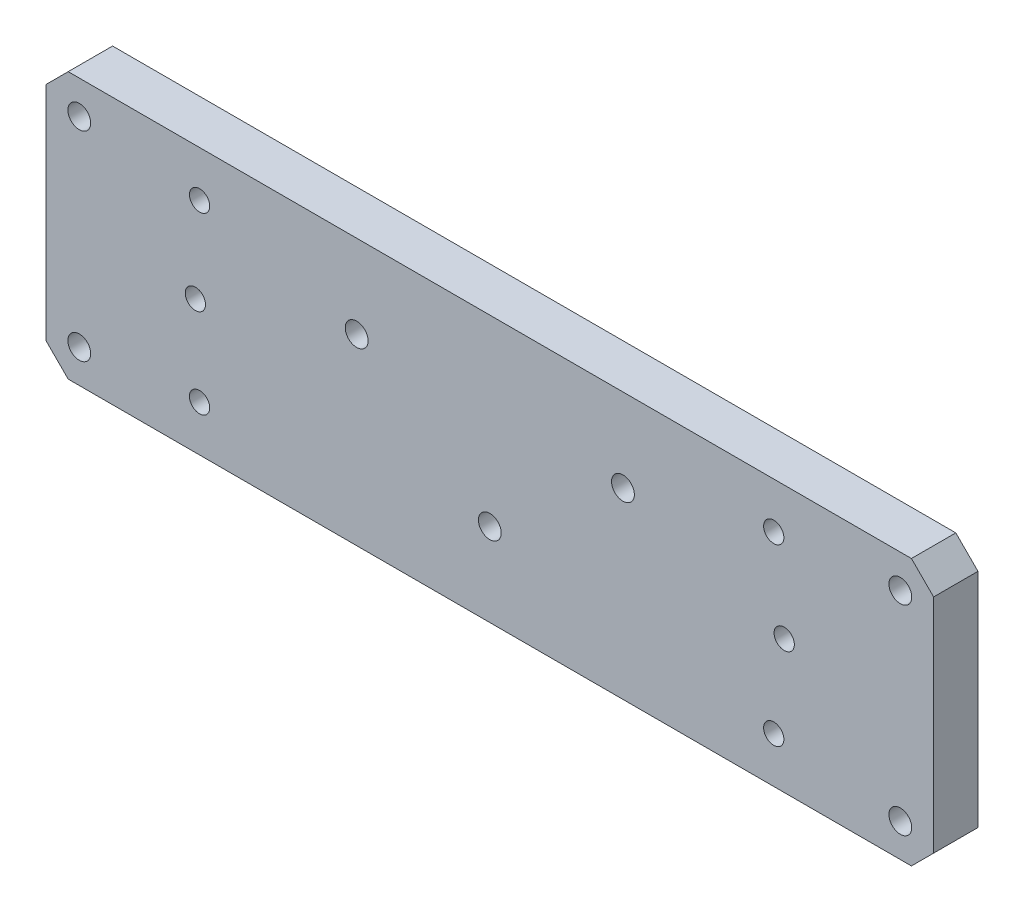
SolidWorks part; units mm, degrees
material "6061-T6 (SS)"
ref_plane "Front Plane" through (0, 0, 0) normal (0, 0, 1) x (1, 0, 0)
ref_plane "Top Plane" through (0, 0, 0) normal (0, 1, 0) x (1, 0, 0)
ref_plane "Right Plane" through (0, 0, 0) normal (1, 0, 0) x (0, 0, -1)
sketch "Sketch1" plane through (0, 0, 0) normal (0, 0, 1) x (1, 0, 0)
  line L1 (127, -38.1) -> (-127, -38.1)
  line L2 (127, -38.1) -> (127, 38.1)
  line L3 (127, 38.1) -> (-127, 38.1)
  line L4 (-127, -38.1) -> (-127, 38.1)
  line L5 (127, -38.1) -> (-127, 38.1) construction
  line L6 (127, 38.1) -> (-127, -38.1) construction
  point P0 (0, 0)
  dimension "D1" = 254
  dimension "D2" = 76.2
extrude "Boss-Extrude1" add sketch "Sketch1" along normal blind 12.7
hole_wizard "1/4 Clearance Hole1" positions "Sketch2" profile "Sketch3" hole size "1/4" standard "ANSI Inch" end condition through all
sketch "Sketch2" plane through (0, 0, 12.7) normal (0, 0, 1) x (1, 0, 0)
  line L0 (-117.475, 38.1) -> (-117.475, -38.1) construction
  line L4 (0, 38.1) -> (0, 0) construction
  line L5 (0, 0) -> (-117.475, 0) construction
  line L7 (-38.1, 0) -> (-38.1, 14.2875) construction
  line L9 (0, 0) -> (0, -14.2875) construction
  line L11 (-117.475, 28.575) -> (-117.475, 0)
  line L13 (-117.475, 14.2875) -> (-38.1, 14.2875) construction
  point P9 (-117.475, -28.575)
  point P11 (-117.475, 28.575)
  point P24 (117.475, -28.575)
  point P26 (117.475, 28.575)
  point P35 (-38.1, 14.2875)
  point P40 (0, -14.2875)
  point P55 (38.1, 14.2875)
sketch "Sketch3" plane through (38.1, 14.2875, 12.7) normal (1, 0, 0) x (0, -1, 0)
  line L0 (0, 0) -> (0, 12.7)
  line L1 (0, 12.7) -> (3.2639, 12.7)
  line L2 (3.2639, 12.7) -> (3.2639, 0)
  line L3 (3.2639, 0) -> (0, 0)
  line L4 (0, -6.35) -> (0, 107.95) construction
  dimension "Thru Hole Dia." = 6.5278
  dimension "Thru Hole Depth" = 12.7
chamfer "Chamfer1" distance 6.35 angle 45 4 edges at (127, 38.1, 6.35) (127, -38.1, 6.35) (-127, 38.1, 6.35) (-127, -38.1, 6.35)
hole_wizard "CSK for M5 Flat Head Machine Screw1" positions "Sketch6" profile "Sketch7" countersink size "M5" standard "ANSI Metric" end condition through all
sketch "Sketch6" plane through (0, 0, 0) normal (0, 0, -1) x (-1, 0, 0)
  line L0 (-81.25, 25) -> (-81.25, -25) construction
  line L1 (83.05, 25) -> (83.05, -25) construction
  point P0 (-81.25, -25)
  point P1 (-81.25, 25)
  point P2 (83.05, 25)
  point P3 (83.05, -25)
  point P4 (-84.25, 0)
  point P5 (84.25, 0)
  point P14 (-81.25, -25)
  point P16 (-81.25, 25)
  point P18 (84.25, 0)
  point P20 (83.05, -25)
  point P22 (83.05, 25)
  point P23 (0, 0)
  point P24 (84.25, 0)
sketch "Sketch7" plane through (81.25, -25, 0) normal (1, 0, 0) x (0, 1, 0)
  line L0 (0, 0) -> (0, 12.7)
  line L1 (0, 12.7) -> (2.9, 12.7)
  line L2 (2.9, 12.7) -> (2.9, 2.3)
  line L3 (2.9, 2.3) -> (5.2, 0)
  line L5 (5.2, 0) -> (0, 0)
  line L6 (-2.9, 2.3) -> (-5.2, 0) construction
  line L11 (0, -6.35) -> (0, 107.95) construction
  dimension "Thru Hole Dia." = 5.8
  dimension "Thru Hole Depth" = 12.7
  dimension "Near C'Sink Dia." = 10.4
  dimension "Near C'Sink Angle" = 90
